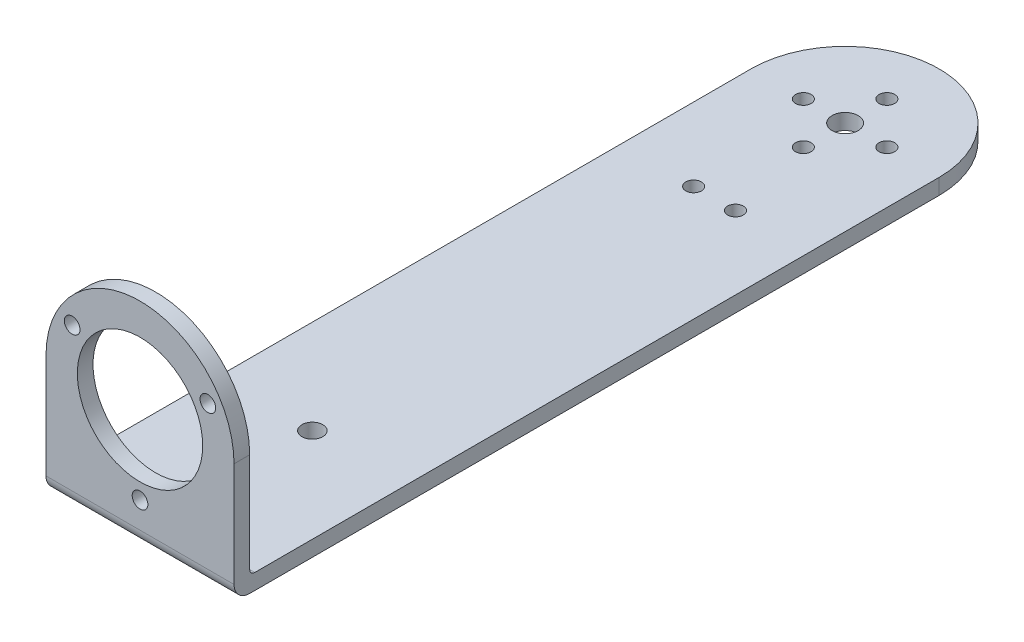
SolidWorks part; units mm, degrees
material "锻制不锈钢"
ref_plane "前视基准面" through (0, 0, 0) normal (0, 0, 1) x (1, 0, 0)
ref_plane "上视基准面" through (0, 0, 0) normal (0, 1, 0) x (1, 0, 0)
ref_plane "右视基准面" through (0, 0, 0) normal (1, 0, 0) x (0, 0, -1)
other "Configuration Table"
sketch "草图1" plane through (0, 0, 0) normal (0, 1, 0) x (1, 0, 0)
  line L0 (0, 0) -> (0, 67.5) construction
  line L1 (18, -67.5) -> (-18, -67.5)
  line L2 (18, -67.5) -> (18, 67.5)
  line L3 (18, 67.5) -> (-18, 67.5)
  line L4 (-18, -67.5) -> (-18, 67.5)
  line L5 (18, -67.5) -> (-18, 67.5) construction
  line L6 (18, 67.5) -> (-18, -67.5) construction
  arc A0 (18, 67.5) -> (-18, 67.5) centre (0, 67.5) ccw
  circle A1 centre (0, 67.5) radius 8 construction
  circle A2 centre (0, 75.5) radius 1.5
  circle A3 centre (0, 59.5) radius 1.5
  circle A4 centre (-8, 67.5) radius 1.5
  circle A5 centre (8, 67.5) radius 1.5
  circle A6 centre (0, 67.5) radius 2.5
  circle A7 centre (-4, 42.5) radius 1.5
  circle A8 centre (4, 42.5) radius 1.5
  circle A9 centre (0, -34.5) radius 2
  point P0 (0, 0)
  dimension "D3" = 25
  dimension "D5" = 102
  dimension "D1" = 135
  dimension "D2" = 36
  dimension "D4" = 4
extrude "凸台-拉伸1" add sketch "草图1" along normal blind 3 contours A6 L3 A4 L4 L1 L2 A5 A9 A3 A7 A8 | A6 L3 A5 A0 A4 A2
sketch "草图2" plane through (0, 3, 0) normal (0, 1, 0) x (1, 0, 0)
  line L0 (18, -67.5) -> (18, 67.5) construction
  line L1 (-18, -67.5) -> (18, -67.5)
  line L2 (-18, -67.5) -> (-18, -64.5)
  line L3 (-18, -64.5) -> (18, -64.5)
  line L4 (18, -67.5) -> (18, -64.5)
  dimension "D1" = 3
extrude "凸台-拉伸2" add sketch "草图2" along normal blind 41
sketch "草图3" plane through (0, 0, 67.5) normal (0, 0, 1) x (1, 0, 0)
  line L0 (0, 44) -> (0, 0) construction
  line L1 (-18, 44) -> (18, 44) construction
  line L2 (18, 44) -> (18, 0) construction
  line L3 (-18, 0) -> (0, 0) construction
  line L4 (-18, 0) -> (-18, 23) construction
  line L5 (-18, 23) -> (0, 23) construction
  line L6 (0, 0) -> (0, 23) construction
  line L11 (-18, 0) -> (18, 0)
  line L12 (18, 0) -> (18, 44)
  line L13 (18, 44) -> (-18, 44)
  line L14 (-18, 44) -> (-18, 0)
  line L15 (-18, 0) -> (18, 0)
  line L16 (18, 0) -> (18, 44)
  line L17 (18, 44) -> (-18, 44)
  line L18 (-18, 44) -> (-18, 0)
  arc A0 (18, 23) -> (-18, 23) centre (0, 23) ccw
  point P15 (0, 41)
  line M11 (18, 44) -> (-18, 44)
  line M12 (-18, 44) -> (-18, 0)
  dimension "D1" = 23
  dimension "D3" = 18
  dimension "D2" = 0
extrude "切除-拉伸1" cut sketch "草图3" against normal blind 4 contours A0 L16 M11 M12
sketch "草图5" plane through (0, 0, 67.5) normal (0, 0, 1) x (1, 0, 0)
  circle A0 centre (0, 23) radius 15 construction
  circle A1 centre (0, 8) radius 1.5
  circle A2 centre (-12.9904, 30.5) radius 1.5
  circle A3 centre (12.9904, 30.5) radius 1.5
  circle A4 centre (0, 23) radius 12
  dimension "D1" = 30
  dimension "D2" = 120
extrude "切除-拉伸2" cut sketch "草图5" against normal blind 4
fillet "圆角1" radius 3 1 edges at (0, 0, 67.5)
fillet "圆角2" radius 1 1 edges at (0, 3, 64.5)
